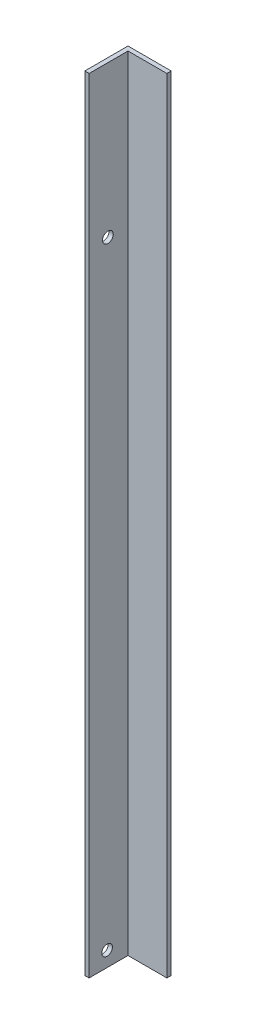
SolidWorks part; units mm, degrees
material "6061 Alloy"
ref_plane "Front Plane" through (0, 0, 0) normal (0, 0, 1) x (1, 0, 0)
ref_plane "Top Plane" through (0, 0, 0) normal (0, 1, 0) x (1, 0, 0)
ref_plane "Right Plane" through (0, 0, 0) normal (1, 0, 0) x (0, 0, -1)
sketch "Sketch1" plane through (0, 0, 0) normal (0, 1, 0) x (1, 0, 0)
  line L0 (-24.9936, -7.8232) -> (-24.9936, 17.5768)
  line L1 (-24.9936, 17.5768) -> (0.4064, 17.5768)
  dimension "D1" = 25.4
  dimension "D2" = 25.4
extrude "Extrude-Thin1" add sketch "Sketch1" along normal blind 460.375 thin
sketch "Sketch3" plane through (-22.4536, 0, 0) normal (1, 0, 0) x (0, 0, -1)
  line L0 (-7.8232, 460.375) -> (15.0368, 460.375) construction
  circle A0 centre (3.2058, 371.475) radius 3.175
  dimension "D1" = 88.9
  dimension "D2" = 6.35
extrude "Cut-Extrude1" cut sketch "Sketch3" against normal through all
sketch "Sketch4" plane through (-22.4536, 0, 0) normal (1, 0, 0) x (0, 0, -1)
  line L0 (-7.8232, 0) -> (15.0368, 0) construction
  circle A0 centre (2.7618, 8.89) radius 3.1119
  dimension "D1" = 8.89
extrude "Cut-Extrude2" cut sketch "Sketch4" against normal through all
